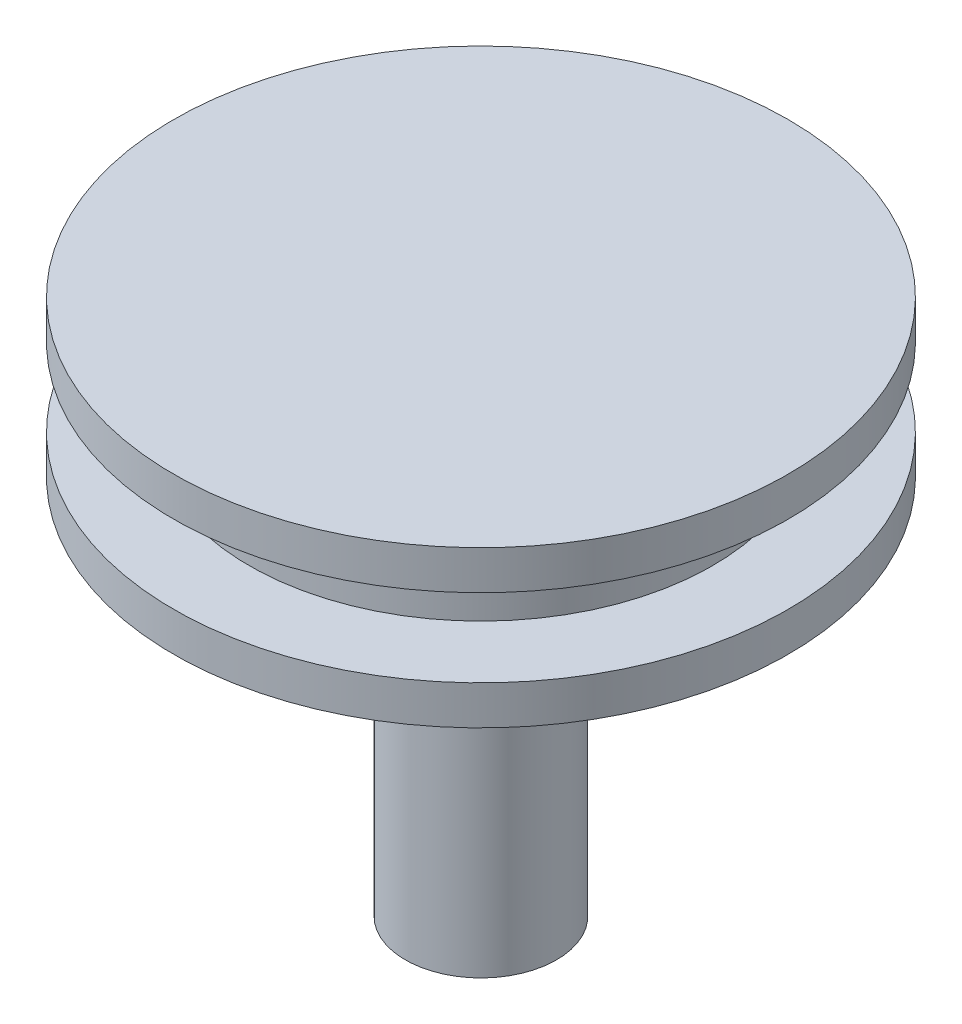
SolidWorks part; units mm, degrees
material "6061 Alloy"
ref_plane "Front Plane" through (0, 0, 0) normal (0, 0, 1) x (1, 0, 0)
ref_plane "Top Plane" through (0, 0, 0) normal (0, 1, 0) x (1, 0, 0)
ref_plane "Right Plane" through (0, 0, 0) normal (1, 0, 0) x (0, 0, -1)
sketch "Sketch1" plane through (0, 0, 0) normal (1, 0, 0) x (0, 0, -1)
  line L0 (0, 0) -> (0, 11)
  line L1 (0, 55) -> (0, -55) construction
  line L2 (0, 11) -> (6.3, 11)
  line L3 (6.3, 11) -> (6.3, 10.2)
  line L4 (6.3, 10.2) -> (4.75, 10.2)
  line L5 (4.75, 10.2) -> (4.75, 8.6)
  line L6 (4.75, 8.6) -> (6.3, 8.6)
  line L7 (6.3, 8.6) -> (6.3, 7.8)
  line L8 (6.3, 7.8) -> (1.55, 7.8)
  line L9 (1.55, 7.8) -> (1.55, 0)
  line L10 (55, 0) -> (-55, 0) construction
  line L11 (1.55, 0) -> (0, 0)
  dimension "D1" = 6.3
  dimension "D2" = 4.75
  dimension "D3" = 1.55
  dimension "D4" = 3.2
  dimension "D5" = 0.8
  dimension "D6" = 0.8
  dimension "D7" = 11
revolve "Revolve1" add sketch "Sketch1" angle 360 about L0
